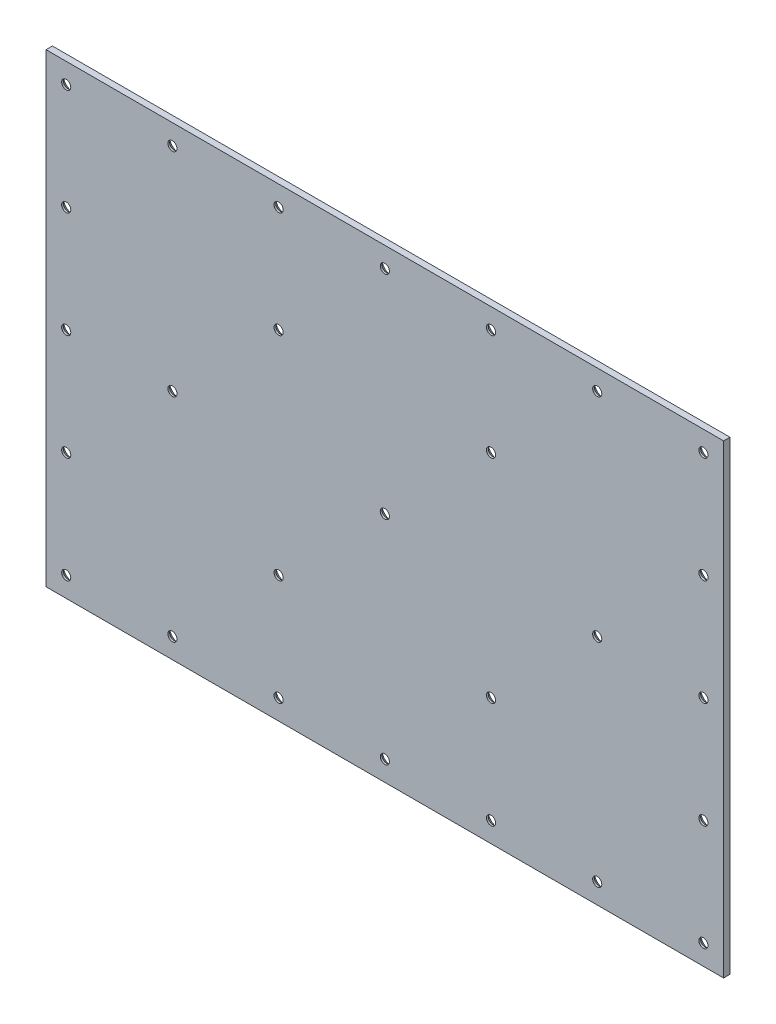
SolidWorks part; units mm, degrees
material "Сталь 40Х13 ГОСТ 5632-72"
ref_plane "Спереди" through (0, 0, 0) normal (0, 0, 1) x (1, 0, 0)
ref_plane "Сверху" through (0, 0, 0) normal (0, 1, 0) x (1, 0, 0)
ref_plane "Справа" through (0, 0, 0) normal (1, 0, 0) x (0, 0, -1)
sketch "Эскиз1" plane through (0, 0, 0) normal (0, 0, 1) x (1, 0, 0)
  line L0 (-150, 100) -> (150, 100) construction
  line L1 (-159.5, -109.5) -> (159.5, -109.5)
  line L2 (-159.5, -109.5) -> (-159.5, 109.5)
  line L3 (-159.5, 109.5) -> (159.5, 109.5)
  line L4 (159.5, -109.5) -> (159.5, 109.5)
  line L5 (-159.5, -109.5) -> (159.5, 109.5) construction
  line L6 (-159.5, 109.5) -> (159.5, -109.5) construction
  line L7 (150, -100) -> (150, 100) construction
  line L8 (-150, -100) -> (150, -100) construction
  line L9 (-150, -100) -> (-150, 100) construction
  circle A0 centre (-150, 100) radius 2 construction
  point P0 (0, 0)
  dimension "D4" = 4
  dimension "D1" = 319
  dimension "D2" = 219
  dimension "D3" = 9.5
extrude "Бобышка-Вытянуть1" add sketch "Эскиз1" along normal blind 3
hole_wizard "Зенковка для винта с полупотайной головкой M42" positions "Эскиз7" profile "Эскиз6" countersink size "M4" standard "ГОСТ" end condition through all
sketch "Эскиз7" plane through (0, 0, 0) normal (0, 0, -1) x (-1, 0, 0)
  point P0 (-150, -100)
sketch "Эскиз6" plane through (150, -100, 0) normal (1, 0, 0) x (0, 1, 0)
  line L0 (0, 0) -> (0, 3)
  line L1 (0, 3) -> (2.15, 3)
  line L2 (2.15, 3) -> (2.15, 2.15)
  line L3 (2.15, 2.15) -> (4.3, 0)
  line L5 (4.3, 0) -> (0, 0)
  line L6 (-2.15, 2.15) -> (-4.3, 0) construction
  line L11 (0, -6.35) -> (0, 107.95) construction
  dimension "Диаметр сквозного отверстия" = 4.3
  dimension "Глубина сквозного отверстия" = 3
  dimension "Диаметр передней зенковки" = 8.6
  dimension "Угол передней зенковки" = 90
pattern_linear "Линейный массив3" count 7 spacing 50 along (-1, 0, 0) count 5 spacing 50 along (0, 1, 0) skipping (1, 1), (1, 3), (2, 2), (3, 1), (3, 3), (4, 2), (5, 1), (5, 3) of "Зенковка для винта с полупотайной головкой M42"
